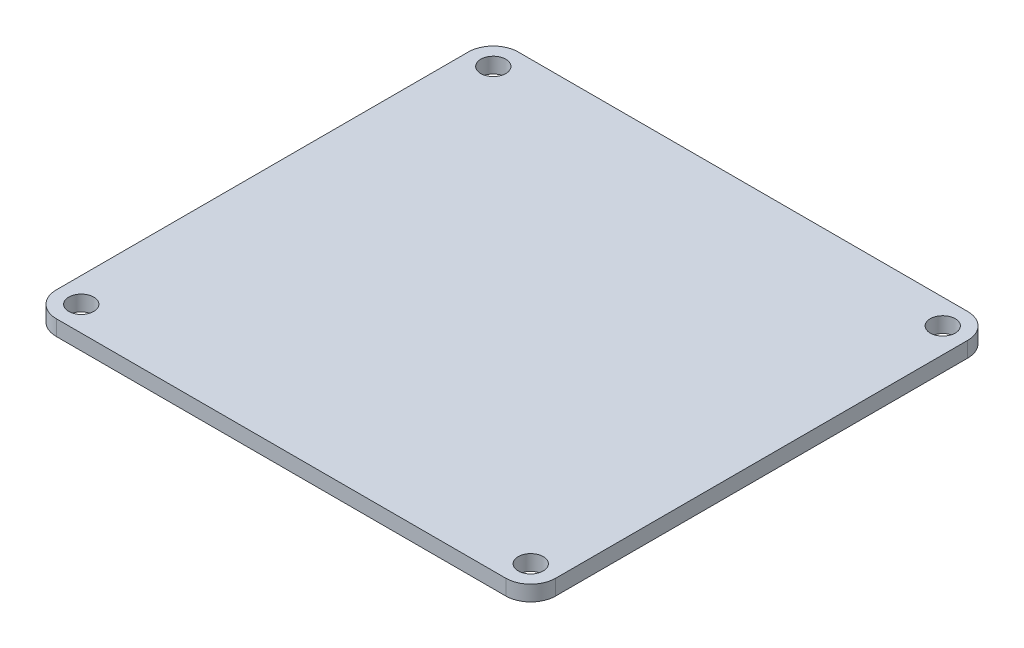
SolidWorks part; units mm, degrees
ref_plane "Front Plane" through (0, 0, 0) normal (0, 0, 1) x (1, 0, 0)
ref_plane "Top Plane" through (0, 0, 0) normal (0, 1, 0) x (1, 0, 0)
ref_plane "Right Plane" through (0, 0, 0) normal (1, 0, 0) x (0, 0, -1)
sketch "Sketch1" plane through (0, 0, 0) normal (0, 1, 0) x (1, 0, 0)
  line L1 (-25.4, -23.495) -> (25.4, -23.495)
  line L2 (-25.4, -23.495) -> (-25.4, 23.495)
  line L3 (-25.4, 23.495) -> (25.4, 23.495)
  line L4 (25.4, -23.495) -> (25.4, 23.495)
  line L5 (-25.4, -23.495) -> (25.4, 23.495) construction
  line L6 (-25.4, 23.495) -> (25.4, -23.495) construction
  point P0 (0, 0)
  dimension "D1" = 50.8
  dimension "D2" = 46.99
extrude "Boss-Extrude1" add sketch "Sketch1" along normal blind 1.57
sketch "Sketch2" plane through (0, 1.57, 0) normal (0, 1, 0) x (1, 0, 0)
  line L0 (-25.4, 23.495) -> (-25.4, -23.495) construction
  line L1 (-22.86, -20.955) -> (22.86, -20.955)
  line L2 (-22.86, -20.955) -> (-22.86, 20.955)
  line L3 (-22.86, 20.955) -> (22.86, 20.955)
  line L4 (22.86, -20.955) -> (22.86, 20.955)
  line L5 (-22.86, -20.955) -> (22.86, 20.955) construction
  line L6 (-22.86, 20.955) -> (22.86, -20.955) construction
  line L7 (-25.4, -23.495) -> (25.4, -23.495) construction
  line L8 (0, -23.495) -> (0, 23.495) construction
  line L9 (25.4, 23.495) -> (-25.4, 23.495) construction
  line L10 (-25.4, 0) -> (25.4, 0) construction
  line L11 (25.4, -23.495) -> (25.4, 23.495) construction
  arc A0 (-25.4, -20.955) -> (-22.86, -23.495) centre (-22.86, -20.955) ccw
  arc A1 (-25.4, 20.955) -> (-22.86, 23.495) centre (-22.86, 20.955) cw
  arc A2 (25.4, 20.955) -> (22.86, 23.495) centre (22.86, 20.955) ccw
  arc A3 (25.4, -20.955) -> (22.86, -23.495) centre (22.86, -20.955) cw
  point P0 (0, 0)
  point P17 (0, 0)
  point P22 (0, 0)
  line M5 (25.4, -23.495) -> (25.4, 23.495)
  line M6 (25.4, 23.495) -> (-25.4, 23.495)
  line M7 (-25.4, 23.495) -> (-25.4, -23.495)
  line M8 (-25.4, -23.495) -> (25.4, -23.495)
  dimension "D1" = 45.72
  dimension "D2" = 41.91
hole_wizard "1/16 (0.1) Dowel Hole1" positions "3DSketch1" profile "Sketch3" hole size "1/16" standard "ANSI Inch" end condition through all
sketch3d "3DSketch1"
  point P0 (-22.86, 1.57, -20.955)
  point P3 (22.86, 1.57, -20.955)
  point P6 (22.86, 1.57, 20.955)
  point P9 (-22.86, 1.57, 20.955)
sketch "Sketch3" plane through (-22.86, 1.57, -20.955) normal (1, 0, 0) x (0, 0, 1)
  line L0 (0, 0) -> (0, 1.57)
  line L1 (0, 1.57) -> (1.27, 1.57)
  line L2 (1.27, 1.57) -> (1.27, 0)
  line L5 (1.27, 0) -> (0, 0)
  line L11 (0, -6.35) -> (0, 107.95) construction
  dimension "Thru Hole Dia." = 2.54
  dimension "Thru Hole Depth" = 1.57
extrude "Cut-Extrude1" cut sketch "Sketch2" against normal through all contours A1 M7 M6 | A2 M5 M6 | A3 M5 M8 | A0 M7 M8
